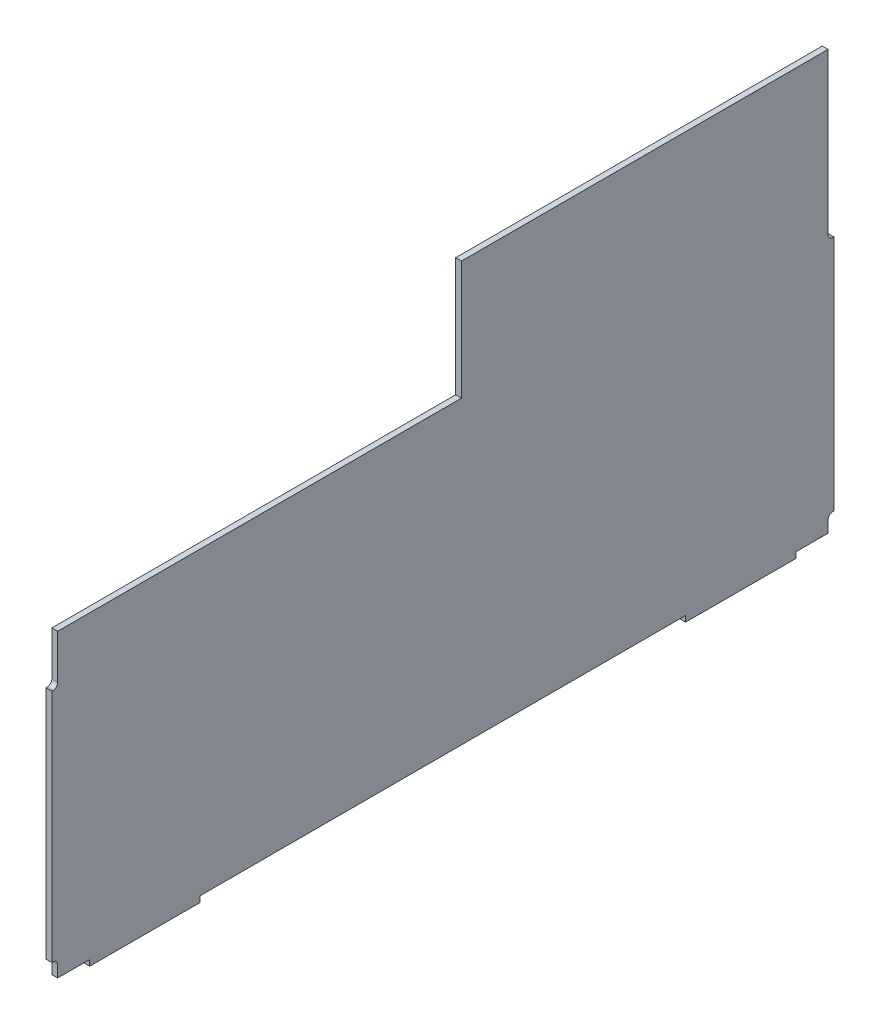
SolidWorks part; units mm, degrees
material "6061-T6 (SS)"
ref_plane "X-Y Datum" through (0, 0, 0) normal (0, 0, 1) x (1, 0, 0)
ref_plane "X-Z Datum" through (0, 0, 0) normal (0, 1, 0) x (1, 0, 0)
ref_plane "Y-Z Datum" through (0, 0, 0) normal (1, 0, 0) x (0, 0, -1)
sketch "Sketch1" plane through (0, 0, 0) normal (1, 0, 0) x (0, 0, -1)
  line L0 (-202.7201, -68.8752) -> (-185.2576, -68.8752)
  line L1 (220.8249, -68.8752) -> (220.8249, 69.5548)
  line L2 (217.6499, 159.7248) -> (17.6249, 159.7248)
  line L3 (17.6249, 159.7248) -> (17.6249, 94.9548)
  line L4 (17.6249, 94.9548) -> (-202.7201, 94.9548)
  line L5 (-205.8951, 68.2848) -> (-205.8951, -59.9852)
  line L6 (-185.2576, -68.8752) -> (-185.2576, -72.0502)
  line L7 (-185.2576, -72.0502) -> (-124.9326, -72.0502)
  line L8 (-124.9326, -72.0502) -> (-124.9326, -68.8752)
  line L9 (0, 55) -> (0, -55) construction
  line L13 (-124.9326, -68.8752) -> (124.9326, -68.8752)
  line L14 (200.1874, -68.8752) -> (220.8249, -68.8752)
  line L15 (217.6499, 159.7248) -> (217.6499, 72.0948)
  line L16 (220.1899, 69.5548) -> (220.8249, 69.5548)
  line L17 (7.4649, -68.8752) -> (7.4649, 159.7248) construction
  line L18 (139.8624, -72.0502) -> (139.8624, -68.8752)
  line L19 (200.1874, -72.0502) -> (139.8624, -72.0502)
  line L20 (200.1874, -68.8752) -> (200.1874, -72.0502)
  line L21 (124.9326, -68.8752) -> (139.8624, -68.8752)
  line L22 (-202.7201, 94.9548) -> (-202.7201, 70.8248)
  line L23 (-205.2601, 68.2848) -> (-205.8951, 68.2848)
  line L24 (-205.8951, -59.9852) -> (-205.2601, -59.9852)
  line L25 (-202.7201, -62.5252) -> (-202.7201, -68.8752)
  line L26 (-205.8951, 77.1748) -> (220.8249, 77.1748) construction
  arc A0 (217.6499, 72.0948) -> (220.1899, 69.5548) centre (220.1899, 72.0948) ccw
  arc A1 (-202.7201, 70.8248) -> (-205.2601, 68.2848) centre (-205.2601, 70.8248) cw
  arc A2 (-205.2601, -59.9852) -> (-202.7201, -62.5252) centre (-205.2601, -62.5252) cw
  point P8 (-202.7201, -59.9852)
  point P22 (217.6499, 69.5548)
  point P30 (-202.7201, 68.2848)
  dimension "D9" = 2.54
  dimension "D13" = 2.54
  dimension "D8" = 2.54
  dimension "D2" = 228.6
  dimension "D3" = 3.175
  dimension "D4" = 60.325
  dimension "D5" = 3.175
  dimension "D6" = 203.2
  dimension "D7" = 90.17
  dimension "D10" = 3.175
  dimension "D11" = 213.36
  dimension "D12" = 8.89
  dimension "D14" = 64.77
  dimension "D15" = 8.89
  dimension "D16" = 146.05
extrude "Boss-Extrude1" add sketch "Sketch1" along normal blind 3.175
sketch "Sketch2" plane through (3.175, 0, 0) normal (1, 0, 0) x (0, 0, -1)
  line L1 (220.8249, -68.8752) -> (217.6499, -68.8752)
  line L2 (220.8249, -68.8752) -> (220.8249, -59.9852)
  line L3 (220.8249, -59.9852) -> (220.1899, -59.9852)
  line L4 (217.6499, -68.8752) -> (217.6499, -62.5252)
  arc A0 (220.1899, -59.9852) -> (217.6499, -62.5252) centre (220.1899, -62.5252) ccw
  dimension "D3" = 2.54
  dimension "D1" = 3.175
  dimension "D2" = 8.89
extrude "Cut-Extrude1" cut sketch "Sketch2" against normal through all both and the other way through all
